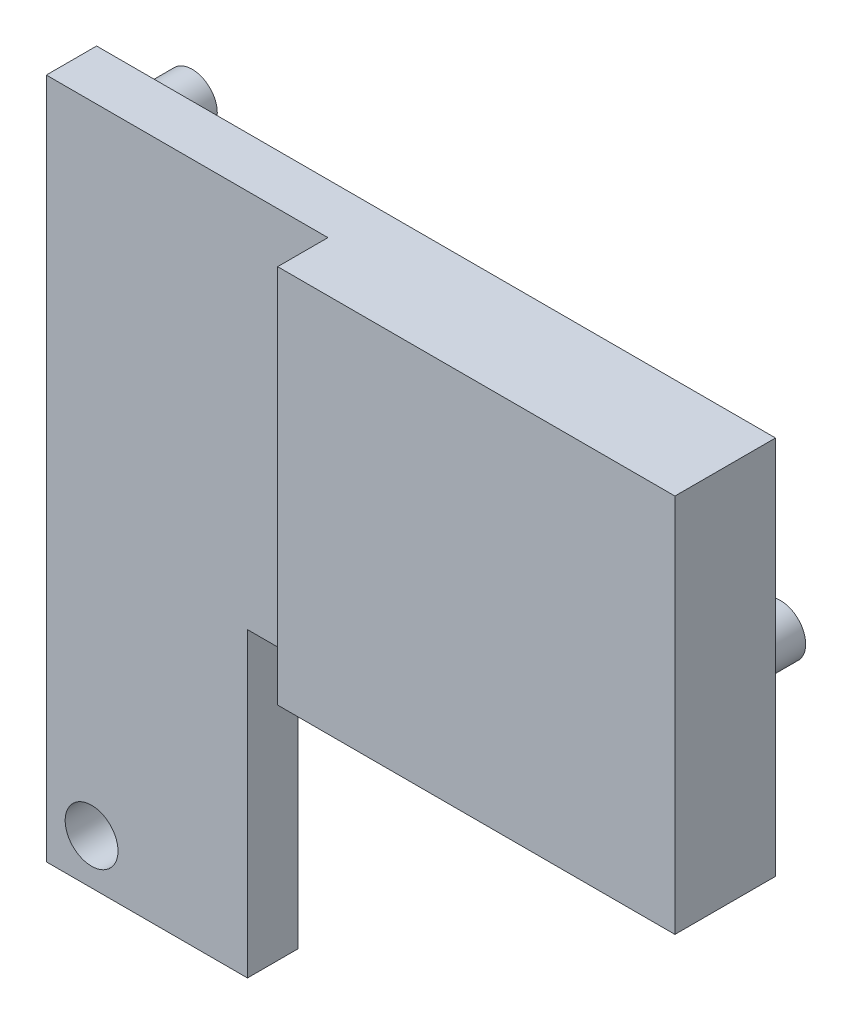
SolidWorks part; units mm, degrees
ref_plane "Front Plane" through (0, 0, 0) normal (0, 0, 1) x (1, 0, 0)
ref_plane "Top Plane" through (0, 0, 0) normal (0, 1, 0) x (1, 0, 0)
ref_plane "Right Plane" through (0, 0, 0) normal (1, 0, 0) x (0, 0, -1)
sketch "Sketch1" plane through (0, 0, 0) normal (0, 0, 1) x (1, 0, 0)
  line L0 (-51.85, -32.1) -> (-51.85, -55.5) construction
  line L1 (-51.85, -55.5) -> (-51.85, -57.3) construction
  line L2 (-51.85, -57.3) -> (-53.65, -57.3) construction
  line L3 (-50.65, -30) -> (-26.15, -30) construction
  line L4 (-53.65, -57.3) -> (-45.65, -57.3)
  line L5 (-53.65, -57.3) -> (-53.65, -30)
  line L6 (-53.65, -30) -> (-26.65, -30)
  line L7 (-26.65, -45.3) -> (-26.65, -30)
  line L8 (-53.65, -57.3) -> (-45.65, -57.3) construction
  line L9 (-45.65, -57.3) -> (-45.65, -45.3)
  line L10 (-45.65, -45.3) -> (-26.65, -45.3)
  circle A2 centre (-51.85, -55.5) radius 1.05
  dimension "D7" = 2.1
  dimension "D1" = 23.4
  dimension "D2" = 1.8
  dimension "D3" = 1.8
  dimension "D4" = 27
  dimension "D8" = 8
  dimension "D9" = 12
extrude "Boss-Extrude1" add sketch "Sketch1" along normal blind 2
sketch "Sketch2" plane through (0, 0, 2) normal (0, 0, 1) x (1, 0, 0)
  circle A0 centre (-28.45, -38.7) radius 1
  circle A1 centre (-51.85, -32.1) radius 1
  dimension "D1" = 2
  dimension "D2" = 2
extrude "Boss-Extrude2" add sketch "Sketch2" against normal blind 4
sketch "Sketch3" plane through (0, 0, 2) normal (0, 0, 1) x (1, 0, 0)
  line L0 (-45.65, -45.3) -> (-26.65, -45.3) construction
  line L1 (-26.65, -30) -> (-42.45, -30)
  line L2 (-26.65, -30) -> (-26.65, -45.3)
  line L3 (-26.65, -45.3) -> (-42.45, -45.3)
  line L4 (-42.45, -30) -> (-42.45, -45.3)
  line L5 (-53.65, -30) -> (-53.65, -57.3) construction
  dimension "D1" = 11.2
extrude "Boss-Extrude3" add sketch "Sketch3" along normal blind 2
sketch "Sketch4" plane through (0, 0, 0) normal (0, 0, -1) x (-1, 0, 0)
  line L0 (53.65, -30) -> (53.65, -57.3) construction
  line L1 (26.65, -30) -> (53.65, -30)
  line L2 (26.65, -30) -> (26.65, -30.2)
  line L3 (26.65, -30.2) -> (53.65, -30.2)
  line L4 (53.65, -30) -> (53.65, -30.2)
  dimension "D1" = 0.2
extrude "Cut-Extrude1" cut sketch "Sketch4" against normal through all
